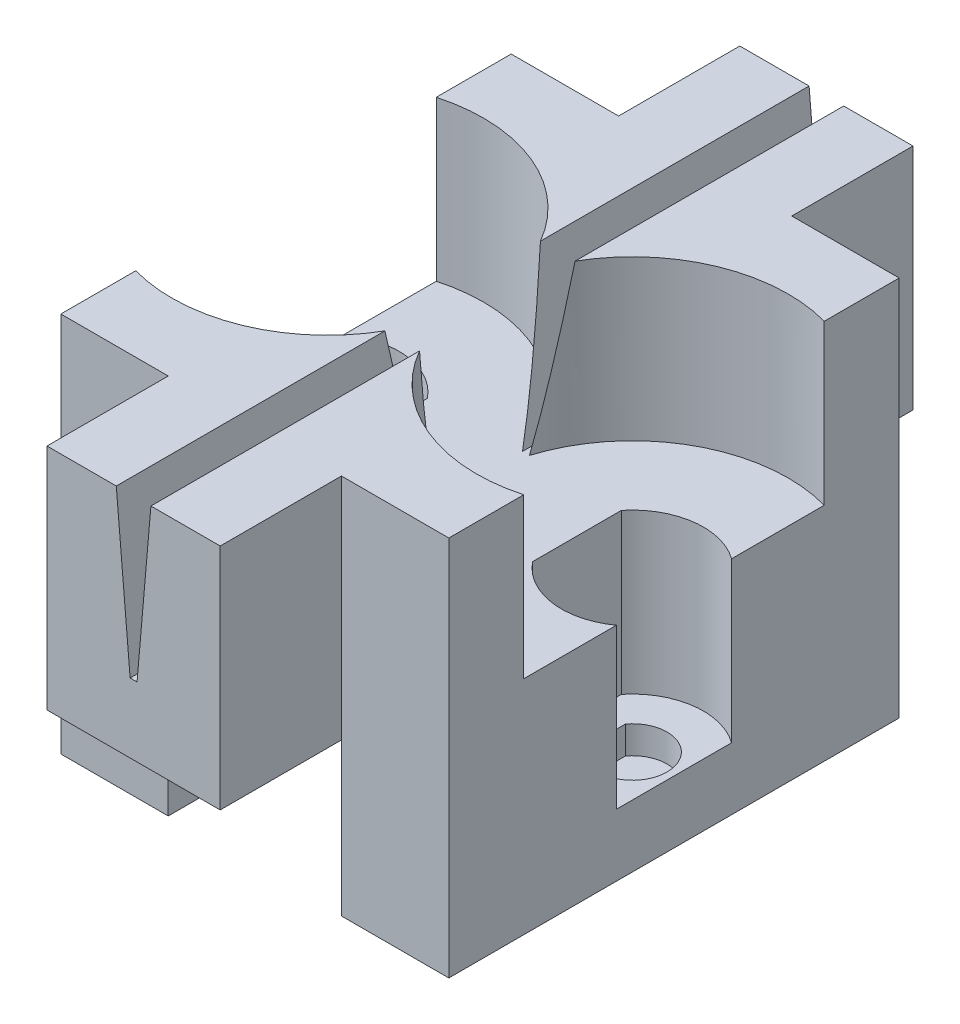
SolidWorks part; units mm, degrees
ref_plane "Front Plane" through (0, 0, 0) normal (0, 0, 1) x (1, 0, 0)
ref_plane "Top Plane" through (0, 0, 0) normal (0, 1, 0) x (1, 0, 0)
ref_plane "Right Plane" through (0, 0, 0) normal (1, 0, 0) x (0, 0, -1)
sketch "Sketch1" plane through (0, 0, 0) normal (0, 1, 0) x (1, 0, 0)
  line L1 (-28, -50) -> (28, -50)
  line L2 (-28, -50) -> (-28, 50)
  line L3 (-28, 50) -> (28, 50)
  line L4 (28, -50) -> (28, 50)
  line L5 (-28, -50) -> (28, 50) construction
  line L6 (-28, 50) -> (28, -50) construction
  point P0 (0, 0)
  dimension "D1" = 100
  dimension "D2" = 56
extrude "Boss-Extrude1" add sketch "Sketch1" along normal blind 55
sketch "Sketch3" plane through (0, 0, 50) normal (0, 0, 1) x (1, 0, 0)
  line L0 (0.5, 55) -> (0.5, 32) construction
  line L1 (-28, 55) -> (28, 55) construction
  line L3 (-28, 55) -> (-28, 0) construction
  line L4 (-0.5, 32) -> (-0.5, 55) construction
  line L5 (28, 55) -> (28, 0) construction
  line L11 (-0.5, 32) -> (-2.5, 55)
  line L13 (2.5, 55) -> (0.5, 32)
  line L14 (-0.5, 32) -> (0.5, 32)
  line L15 (-2.5, 55) -> (2.5, 55)
  dimension "D1" = 23
  dimension "D2" = 28.5
  dimension "D3" = 23
  dimension "D4" = 28.5
  dimension "D5" = 5
  dimension "D6" = 2
extrude "Cut-Extrude2" cut sketch "Sketch3" against normal through all
sketch "Sketch7" plane through (0, 55, 0) normal (0, 1, 0) x (1, 0, 0)
  line L0 (-0.5, 50) -> (-0.5, -50) construction
  line L3 (28, 50) -> (2.5, 50) construction
  circle A0 centre (22, 0) radius 10
  circle A1 centre (22, 0) radius 21.5 construction
  circle A2 centre (22, 0) radius 22.5
  dimension "D1" = 20
  dimension "D3" = 43
  dimension "D4" = 1
  dimension "D5" = 50
  dimension "D2" = 22.5
extrude "Cut-Extrude4" cut sketch "Sketch7" against normal blind 23
sketch "Sketch9" plane through (0, 55, 0) normal (0, 1, 0) x (1, 0, 0)
  line L0 (14, 6.408) -> (14, -6.408)
  circle A0 centre (22, 0) radius 10.25 construction
  arc A1 (14, 6.408) -> (14, -6.408) centre (22, 0) cw
  circle A2 centre (22, 0) radius 22.5 construction
  dimension "D1" = 20.5
  dimension "D2" = 8
extrude "Cut-Extrude5" cut sketch "Sketch9" against normal blind 46
sketch "Sketch10" plane through (0, 9, 0) normal (0, 1, 0) x (1, 0, 0)
  line L0 (18, 3) -> (18, -3)
  arc A1 (18, 3) -> (18, -3) centre (22, 0) cw
  arc A2 (28, 8.3104) -> (14, 6.408) centre (22, 0) ccw construction
  dimension "D1" = 6
  dimension "D2" = 5
  dimension "D3" = 0
  dimension "D4" = 0
extrude "Cut-Extrude6" cut sketch "Sketch10" against normal blind 4
sketch "Sketch11" plane through (0, 55, 0) normal (0, 1, 0) x (1, 0, 0)
  line L0 (14, 6.408) -> (14, -6.408)
  arc A0 (14, 6.408) -> (14, -6.408) centre (21.6771, 0) ccw
extrude "Cut-Extrude7" cut sketch "Sketch11" against normal blind 23
mirror "Mirror1" about plane through (0, 0, 0) normal (1, 0, 0) of "Cut-Extrude7", "Cut-Extrude4", "Cut-Extrude5", "Cut-Extrude6"
sketch "Sketch12" plane through (0, 55, 0) normal (0, 1, 0) x (1, 0, 0)
  line L0 (-2.5, 50) -> (-2.5, 11.225) construction
  line L1 (-28, 50) -> (-12.5, 50)
  line L2 (-28, 50) -> (-28, 32.5)
  line L3 (-28, 32.5) -> (-12.5, 32.5)
  line L4 (-12.5, 50) -> (-12.5, 32.5)
  line L5 (28, 50) -> (12.5, 50)
  line L6 (28, 50) -> (28, 32.5)
  line L7 (28, 32.5) -> (12.5, 32.5)
  line L8 (12.5, 50) -> (12.5, 32.5)
  line L9 (-28, -50) -> (-12.5, -50)
  line L10 (-28, -50) -> (-28, -32.5)
  line L11 (-28, -32.5) -> (-12.5, -32.5)
  line L12 (-12.5, -50) -> (-12.5, -32.5)
  line L13 (28, -50) -> (12.5, -50)
  line L14 (28, -50) -> (28, -32.5)
  line L15 (28, -32.5) -> (12.5, -32.5)
  line L16 (12.5, -50) -> (12.5, -32.5)
  line L17 (2.5, 50) -> (2.5, 11.225) construction
  line L18 (2.5, -11.225) -> (2.5, -50) construction
  line L19 (-2.5, -11.225) -> (-2.5, -50) construction
  arc A1 (-28, -21.6852) -> (-2.5, -11.225) centre (-22, 0) ccw construction
  arc A2 (0.5, -6.6332) -> (28, -21.6852) centre (22, 0) ccw construction
  arc A3 (28, 21.6852) -> (2.5, 11.225) centre (22, 0) ccw construction
  arc A4 (-2.5, 11.225) -> (-28, 21.6852) centre (-22, 0) ccw construction
  dimension "D5" = 32.5
  dimension "D1" = 10
  dimension "D2" = 10
  dimension "D3" = 10
  dimension "D4" = 10
  dimension "D6" = 32.5
  dimension "D7" = 32.5
  dimension "D8" = 32.5
extrude "Cut-Extrude8" cut sketch "Sketch12" against normal through all
sketch "Sketch13" plane through (0, 0, 50) normal (0, 0, 1) x (1, 0, 0)
  line L0 (12.5, 0) -> (12.5, 55) construction
  line L1 (-12.5, 0) -> (12.5, 0)
  line L2 (-12.5, 0) -> (-12.5, 22)
  line L3 (-12.5, 22) -> (12.5, 22)
  line L4 (12.5, 0) -> (12.5, 22)
  dimension "D1" = 22
extrude "Cut-Extrude9" cut sketch "Sketch13" against normal through all
